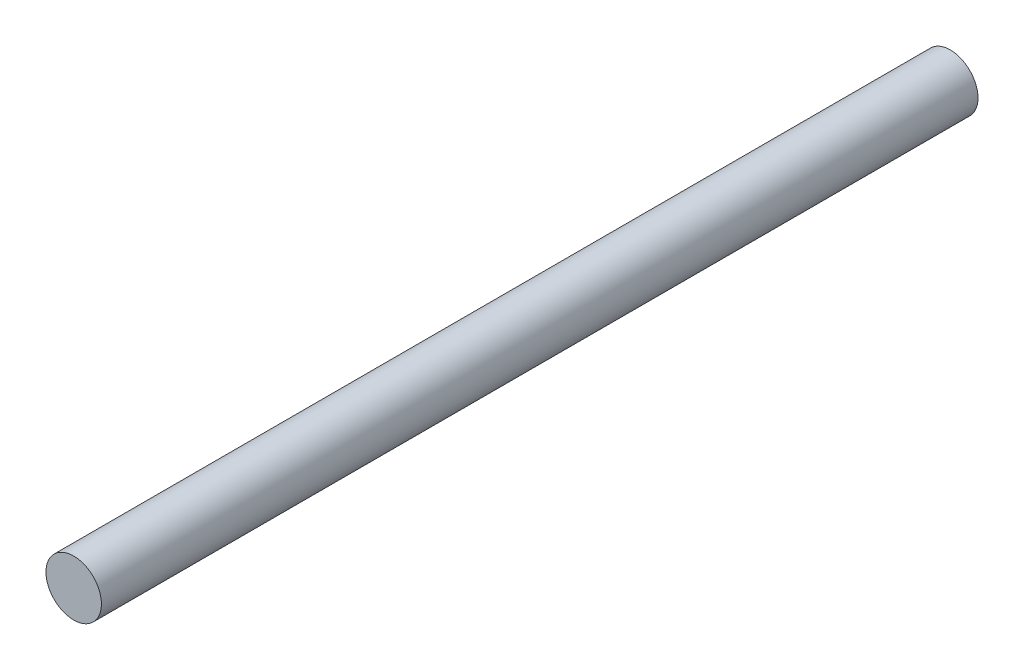
SolidWorks part; units mm, degrees
ref_plane "Front Plane" through (0, 0, 0) normal (0, 0, 1) x (1, 0, 0)
ref_plane "Top Plane" through (0, 0, 0) normal (0, 1, 0) x (1, 0, 0)
ref_plane "Right Plane" through (0, 0, 0) normal (1, 0, 0) x (0, 0, -1)
sketch "Sketch1" plane through (0, 0, 0) normal (0, 0, 1) x (1, 0, 0)
  circle A0 centre (0, 0) radius 3.175
  dimension "D1" = 6.35
extrude "Boss-Extrude1" add sketch "Sketch1" along normal blind 100.33 contours A0
